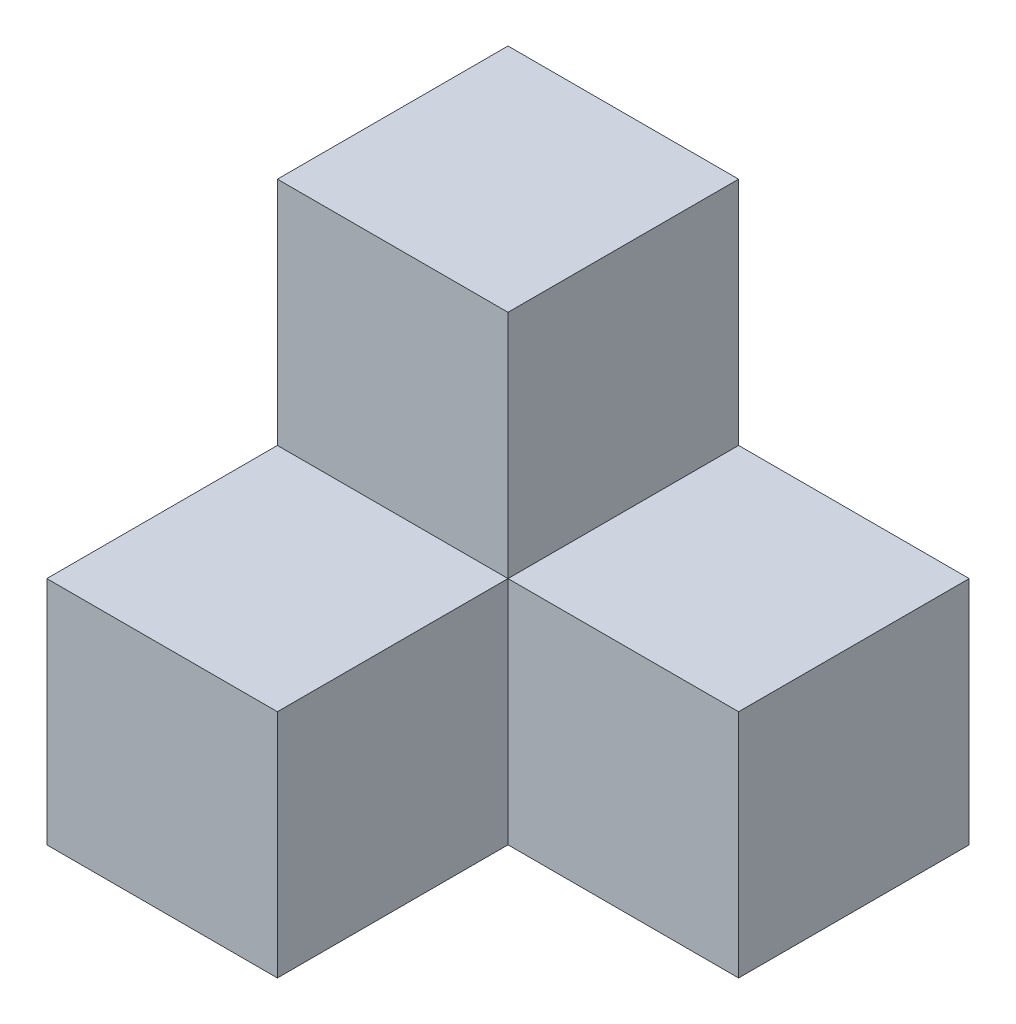
SolidWorks part; units mm, degrees
ref_plane "Plan de face" through (0, 0, 0) normal (0, 0, 1) x (1, 0, 0)
ref_plane "Plan de dessus" through (0, 0, 0) normal (0, 1, 0) x (1, 0, 0)
ref_plane "Plan de droite" through (0, 0, 0) normal (1, 0, 0) x (0, 0, -1)
sketch "Esquisse1" plane through (0, 0, 0) normal (0, 0, 1) x (1, 0, 0)
  line L0 (0, 0) -> (0, 20)
  line L1 (0, 20) -> (10, 20)
  line L2 (10, 20) -> (10, 10)
  line L3 (10, 10) -> (20, 10)
  line L4 (20, 10) -> (20, 0)
  line L5 (20, 0) -> (0, 0)
  dimension "D1" = 20
  dimension "D2" = 10
  dimension "D3" = 20
  dimension "D4" = 10
extrude "Boss.-Extru.1" add sketch "Esquisse1" along normal blind 10
sketch "Esquisse2" plane through (0, 0, 10) normal (0, 0, 1) x (1, 0, 0)
  line L1 (0, 0) -> (10, 0)
  line L2 (0, 0) -> (0, 10)
  line L3 (0, 10) -> (10, 10)
  line L4 (10, 0) -> (10, 10)
  dimension "D1" = 10
  dimension "D2" = 10
extrude "Boss.-Extru.2" add sketch "Esquisse2" along normal blind 10
